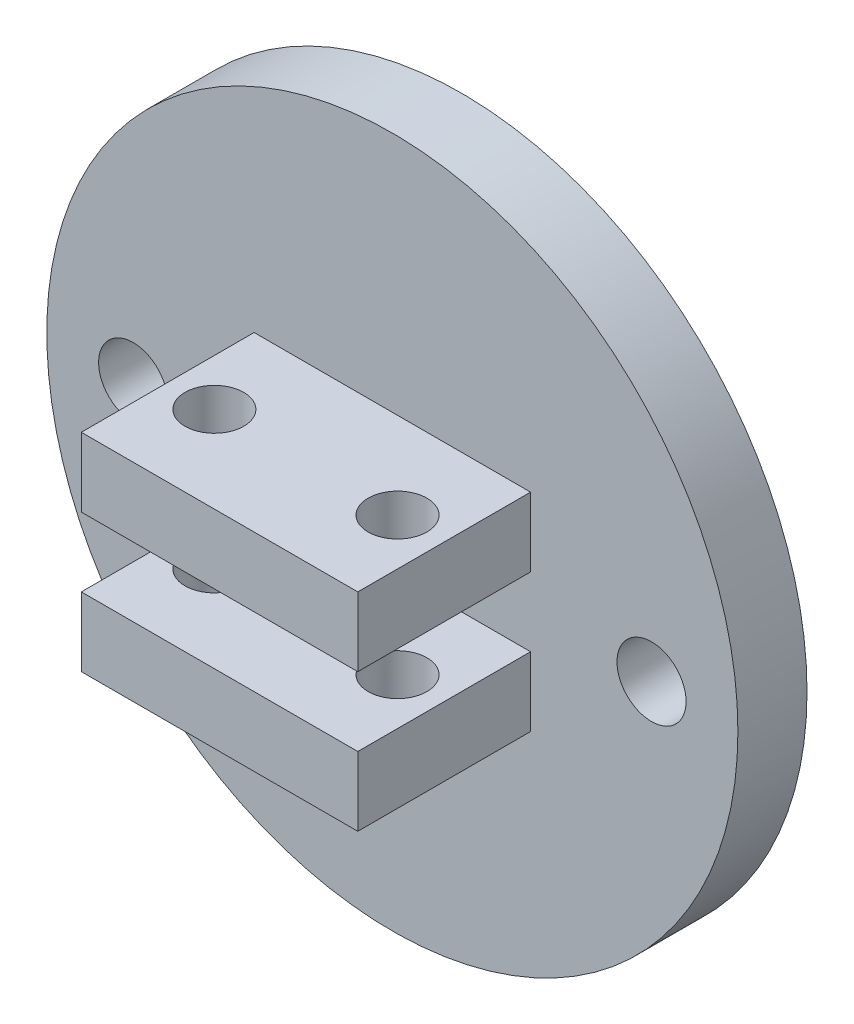
SolidWorks part; units mm, degrees
ref_plane "Alzado" through (0, 0, 0) normal (0, 0, 1) x (1, 0, 0)
ref_plane "Planta" through (0, 0, 0) normal (0, 1, 0) x (1, 0, 0)
ref_plane "Vista lateral" through (0, 0, 0) normal (1, 0, 0) x (0, 0, -1)
sketch "Croquis1" plane through (0, 0, 0) normal (0, 0, 1) x (1, 0, 0)
  line L0 (-7.5, 0) -> (7.5, 0) construction
  circle A3 centre (0, 0) radius 10
  circle A4 centre (-7.5, 0) radius 1
  circle A5 centre (7.5, 0) radius 1
  point P5 (0, 0)
  dimension "D1" = 20
  dimension "D3" = 2
  dimension "D4" = 2
  dimension "D2" = 15
extrude "Saliente-Extruir1" add sketch "Croquis1" along normal blind 2
sketch "Croquis2" plane through (0, 0, 2) normal (0, 0, 1) x (1, 0, 0)
  line L1 (-4, 1) -> (4, 1)
  line L2 (-4, 1) -> (-4, -1)
  line L3 (-4, -1) -> (4, -1)
  line L4 (4, 1) -> (4, -1)
  line L5 (-4, 1) -> (4, 1)
  line L6 (-4, 1) -> (-4, 3)
  line L7 (-4, 3) -> (4, 3)
  line L8 (4, 1) -> (4, 3)
  line L9 (-4, -1) -> (4, -1)
  line L10 (-4, -1) -> (-4, -3)
  line L11 (-4, -3) -> (4, -3)
  line L12 (4, -1) -> (4, -3)
  point P8 (0, 1)
  point P10 (-4, 0)
  dimension "D1" = 2
  dimension "D2" = 2
  dimension "D3" = 2
  dimension "D4" = 8
extrude "Saliente-Extruir2" add sketch "Croquis2" along normal blind 5 contours L1 L8 L7 L6 | L12 L3 L10 L11
sketch "Croquis3" plane through (0, -3, 0) normal (0, -1, 0) x (-1, 0, 0)
  line L0 (-2.65, -4.5) -> (2.65, -4.5) construction
  line L2 (-4, -7) -> (-4, -2) construction
  line L3 (4, -7) -> (-4, -7) construction
  point P0 (-2.65, -4.5)
  point P2 (2.65, -4.5)
  point P10 (-4, -4.5)
  point P13 (0, -7)
  point P14 (0, -4.5)
  dimension "D1" = 5.3
hole_wizard "Taladro de margen para M1.61" positions "Croquis3" profile "Croquis4" hole size "M1.6" standard "Ansi Metric" end condition through all
sketch "Croquis4" plane through (2.65, -3, 4.5) normal (1, 0, 0) x (0, 0, -1)
  line L0 (0, 0) -> (0, 13)
  line L1 (0, 13) -> (0.85, 13)
  line L2 (0.85, 13) -> (0.85, 0.0288)
  line L3 (0.85, 0.0288) -> (0.875, 0)
  line L5 (0.875, 0) -> (0, 0)
  line L6 (-0.85, 0.0288) -> (-0.875, 0) construction
  line L11 (0, -6.35) -> (0, 107.95) construction
  dimension "Diámetro de taladro hasta el siguiente" = 1.7
  dimension "Profundidad de taladro hasta el siguiente" = 13
  dimension "Diámetro de avellanado cercano" = 1.75
  dimension "Ángulo de avellanado cercano" = 82
